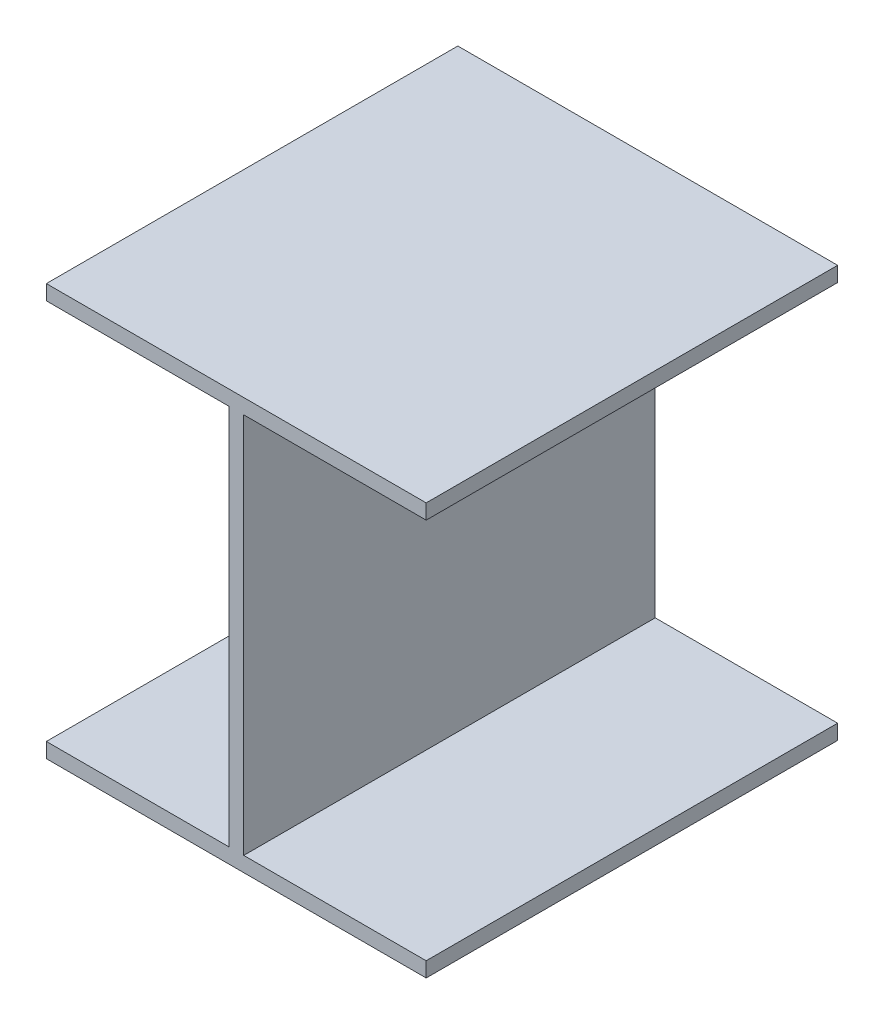
SolidWorks part; units mm, degrees
ref_plane "Front Plane" through (0, 0, 0) normal (0, 0, 1) x (1, 0, 0)
ref_plane "Top Plane" through (0, 0, 0) normal (0, 1, 0) x (1, 0, 0)
ref_plane "Right Plane" through (0, 0, 0) normal (1, 0, 0) x (0, 0, -1)
sketch "Sketch1" plane through (0, 0, 0) normal (0, 0, 1) x (1, 0, 0)
  line L1 (-76.2, 82.55) -> (76.2, 82.55)
  line L2 (-76.2, 76.55) -> (-3, 76.55)
  line L3 (-76.2, -82.55) -> (76.2, -82.55) construction
  line L4 (-76.2, -76.55) -> (-3, -76.55)
  line L5 (-76.2, 82.55) -> (-70.6615, 76.55) construction
  line L6 (-76.2, -82.55) -> (-70.6615, -76.55) construction
  line L7 (-3, 76.55) -> (-3, -76.55)
  line L8 (3, 76.55) -> (3, -76.55)
  line L9 (-76.2, 82.55) -> (-76.2, 76.55)
  line L10 (-76.2, 76.55) -> (-76.1941, 76.5423)
  line L11 (76.2, 82.55) -> (76.2, 76.55)
  line L12 (-76.2, -76.55) -> (-76.2, -82.55)
  line L13 (-76.2, -82.55) -> (76.2, -82.55)
  line L14 (76.2, -82.55) -> (76.2, -76.55)
  line L16 (70.6615, 76.55) -> (76.2, 82.55) construction
  line L17 (70.6615, -76.55) -> (76.2, -82.55) construction
  line L18 (3, 76.55) -> (76.2, 76.55)
  line L19 (-76.2, 76.55) -> (76.2, 76.55) construction
  line L20 (3, -76.55) -> (76.2, -76.55)
  line L21 (-76.2, -76.55) -> (76.2, -76.55) construction
  point P0 (0, 0)
  dimension "D1" = 165.1
  dimension "D2" = 152.4
extrude "Boss-Extrude1" add sketch "Sketch1" along normal blind 165.1 contours L20 L8 L18 L11 L1 L9 L2 L7 L4 L12 L13 L14
